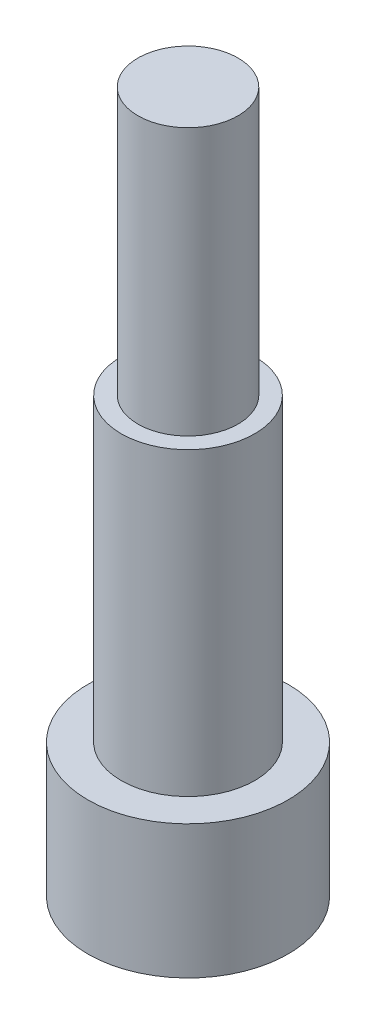
SolidWorks part; units mm, degrees
ref_plane "Front Plane" through (0, 0, 0) normal (0, 0, 1) x (1, 0, 0)
ref_plane "Top Plane" through (0, 0, 0) normal (0, 1, 0) x (1, 0, 0)
ref_plane "Right Plane" through (0, 0, 0) normal (1, 0, 0) x (0, 0, -1)
sketch "Sketch1" plane through (0, 0, 0) normal (0, 0, 1) x (1, 0, 0)
  line L0 (0, 0) -> (3, 0)
  line L1 (3.3, 0) -> (-3.3, 0) construction
  line L2 (3, 0) -> (3, 4)
  line L3 (3, 4) -> (2, 4)
  line L4 (2, 4) -> (2, 13)
  line L5 (2, 13) -> (1.5, 13)
  line L6 (0, -3.3) -> (0, 3.3) construction
  line L7 (0, 21) -> (0, 0)
  line L8 (1.5, 13) -> (1.5, 21)
  line L9 (1.5, 21) -> (0, 21)
  dimension "D1" = 4
  dimension "D2" = 3
  dimension "D3" = 2
  dimension "D4" = 1.5
  dimension "D5" = 17
  dimension "D6" = 8
revolve "Revolve1" add sketch "Sketch1" angle 360 about L7
sketch "Sketch2" plane through (0, 0, 0) normal (0, -1, 0) x (1, 0, 0)
  line L1 (0, -1.7321) -> (1.5, -0.866)
  line L2 (1.5, -0.866) -> (1.5, 0.866)
  line L3 (1.5, 0.866) -> (0, 1.7321)
  line L4 (0, 1.7321) -> (-1.5, 0.866)
  line L5 (-1.5, 0.866) -> (-1.5, -0.866)
  line L6 (-1.5, -0.866) -> (0, -1.7321)
  circle A0 centre (0, 0) radius 1.5 construction
  dimension "D1" = 3
extrude "Cut-Extrude1" cut sketch "Sketch2" against normal blind 2
